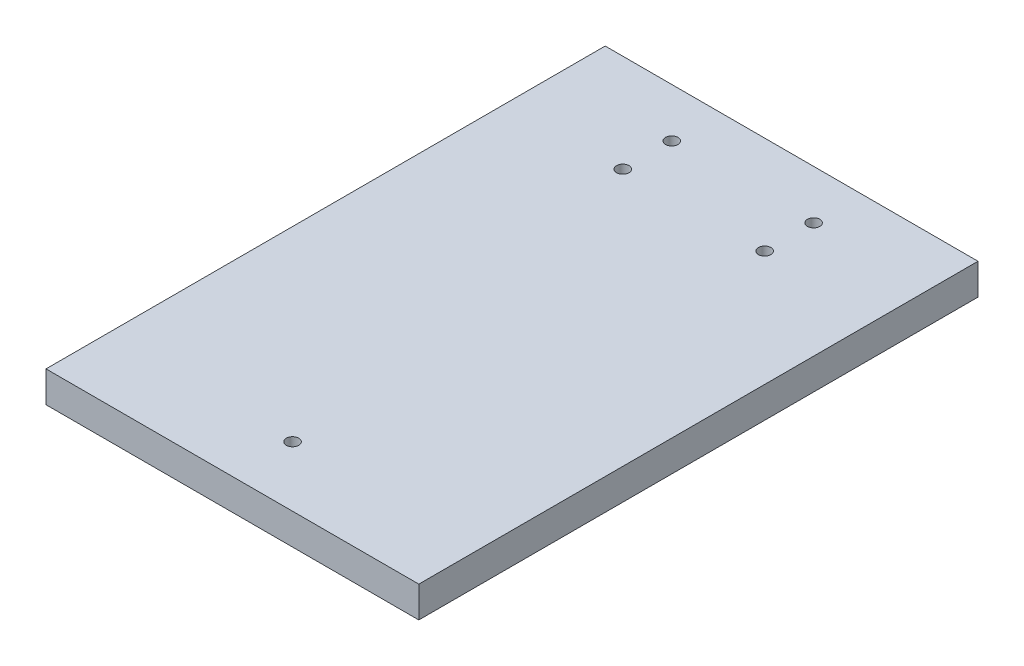
SolidWorks part; units mm, degrees
ref_plane "Front Plane" through (0, 0, 0) normal (0, 0, 1) x (1, 0, 0)
ref_plane "Top Plane" through (0, 0, 0) normal (0, 1, 0) x (1, 0, 0)
ref_plane "Right Plane" through (0, 0, 0) normal (1, 0, 0) x (0, 0, -1)
sketch "Sketch1" plane through (0, 0, 0) normal (0, 1, 0) x (1, 0, 0)
  line L0 (0, -57.15) -> (0, 57.15) construction
  line L1 (-38.1, -57.15) -> (38.1, -57.15)
  line L2 (-38.1, -57.15) -> (-38.1, 57.15)
  line L3 (-38.1, 57.15) -> (38.1, 57.15)
  line L4 (38.1, -57.15) -> (38.1, 57.15)
  line L5 (-38.1, -57.15) -> (38.1, 57.15) construction
  line L6 (-38.1, 57.15) -> (38.1, -57.15) construction
  circle A0 centre (-14.5, 47.15) radius 1.27
  circle A1 centre (14.5, 47.15) radius 1.27
  circle A2 centre (0, -44.85) radius 1.27
  circle A3 centre (-14.5, 37.15) radius 1.27
  circle A4 centre (14.5, 37.15) radius 1.27
  point P0 (0, 0)
  dimension "D1" = 2.54
  dimension "D2" = 76.2
  dimension "D3" = 114.3
  dimension "D4" = 29
  dimension "D5" = 82
  dimension "D6" = 10
  dimension "D7" = 10
extrude "Boss-Extrude1" add sketch "Sketch1" along normal blind 6.35
